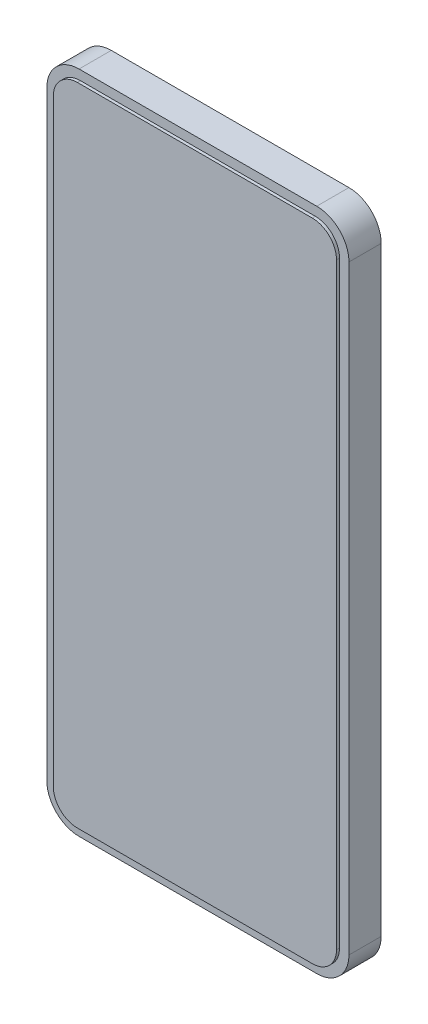
SolidWorks part; units mm, degrees
ref_plane "Front Plane" through (0, 0, 0) normal (0, 0, 1) x (1, 0, 0)
ref_plane "Top Plane" through (0, 0, 0) normal (0, 1, 0) x (1, 0, 0)
ref_plane "Right Plane" through (0, 0, 0) normal (1, 0, 0) x (0, 0, -1)
sketch "Sketch1" plane through (0, 0, 0) normal (0, 0, 1) x (1, 0, 0)
  line L1 (-37.5, -82.5) -> (37.5, -82.5)
  line L2 (-37.5, -82.5) -> (-37.5, 82.5)
  line L3 (-37.5, 82.5) -> (37.5, 82.5)
  line L4 (37.5, -82.5) -> (37.5, 82.5)
  line L5 (-37.5, -82.5) -> (37.5, 82.5) construction
  line L6 (-37.5, 82.5) -> (37.5, -82.5) construction
  point P0 (0, 0)
  dimension "D1" = 165
  dimension "D2" = 75
extrude "Boss-Extrude1" add sketch "Sketch1" along normal blind 8
fillet "Fillet1" radius 8 4 edges at (-37.5, -82.5, 4) (37.5, -82.5, 4) (-37.5, 82.5, 4) (37.5, 82.5, 4)
sketch "Sketch2" plane through (0, 0, 0) normal (0, 0, -1) x (-1, 0, 0)
  line L0 (-29.5, 82.5) -> (29.5, 82.5) construction
  line L1 (-30.5, 75.5) -> (-8.5, 75.5)
  line L2 (-30.5, 75.5) -> (-30.5, 40.5)
  line L3 (-30.5, 40.5) -> (-8.5, 40.5)
  line L4 (-8.5, 75.5) -> (-8.5, 40.5)
  line L5 (-30.5, 75.5) -> (-8.5, 40.5) construction
  line L6 (-30.5, 40.5) -> (-8.5, 75.5) construction
  line L7 (-37.5, -74.5) -> (-37.5, 74.5) construction
  point P0 (-19.5, 58)
  dimension "D1" = 22
  dimension "D2" = 35
  dimension "D3" = 7
  dimension "D4" = 7
extrude "Boss-Extrude2" add sketch "Sketch2" along normal blind 1
fillet "Fillet2" radius 6 4 edges at (30.5, 40.5, -0.5) (8.5, 40.5, -0.5) (30.5, 75.5, -0.5) (8.5, 75.5, -0.5)
sketch "Sketch3" plane through (0, 0, -1) normal (0, 0, -1) x (-1, 0, 0)
  line L0 (-14.5, 75.5) -> (-24.5, 75.5) construction
  circle A0 centre (-23.0437, 68) radius 5
  circle A1 centre (-23.0437, 57) radius 4
  circle A2 centre (-23.0437, 47) radius 4
  circle A3 centre (-13.0437, 68) radius 1.8593
  dimension "D1" = 10
  dimension "D2" = 8
  dimension "D3" = 8
  dimension "D4" = 7.5
  dimension "D5" = 11
  dimension "D6" = 10
  dimension "D7" = 10
extrude "Cut-Extrude1" cut sketch "Sketch3" against normal blind 0.5
sketch "Sketch4" plane through (0, 0, 8) normal (0, 0, 1) x (1, 0, 0)
  line L1 (35.1569, -80.1569) -> (-35.1569, -80.1569)
  line L2 (35.1569, -80.1569) -> (35.1569, 80.1569)
  line L3 (35.1569, 80.1569) -> (-35.1569, 80.1569)
  line L4 (-35.1569, -80.1569) -> (-35.1569, 80.1569)
  line L5 (35.1569, -80.1569) -> (-35.1569, 80.1569) construction
  line L6 (35.1569, 80.1569) -> (-35.1569, -80.1569) construction
  arc A0 (-29.5, 82.5) -> (-37.5, 74.5) centre (-29.5, 74.5) ccw construction
  point P0 (0, 0)
extrude "Boss-Extrude3" add sketch "Sketch4" along normal blind 0.75
fillet "Fillet3" radius 6 4 edges at (-35.1569, -80.1569, 8.375) (35.1569, -80.1569, 8.375) (-35.1569, 80.1569, 8.375) (35.1569, 80.1569, 8.375)
sketch "Sketch5" plane through (0, 0, 0) normal (0, 0, -1) x (-1, 0, 0)
  circle A0 centre (0, 0) radius 8.7009
